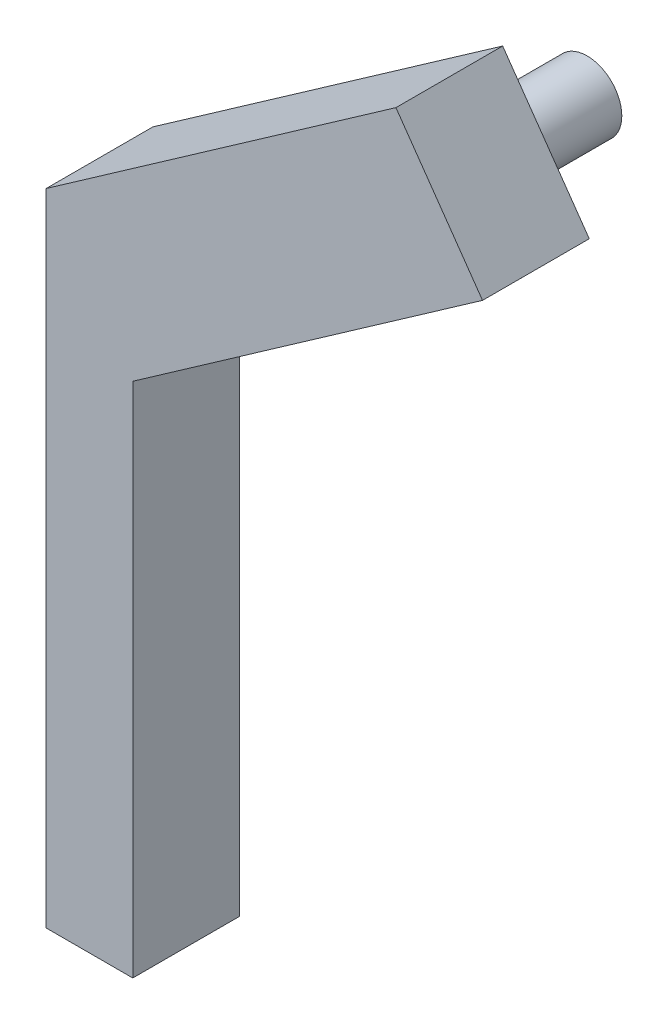
SolidWorks part; units mm, degrees
ref_plane "Front Plane" through (0, 0, 0) normal (0, 0, 1) x (1, 0, 0)
ref_plane "Top Plane" through (0, 0, 0) normal (0, 1, 0) x (1, 0, 0)
ref_plane "Right Plane" through (0, 0, 0) normal (1, 0, 0) x (0, 0, -1)
sketch "Sketch1" plane through (0, 0, 0) normal (0, 0, 1) x (1, 0, 0)
  line L0 (32.8506, -30.613) -> (65.6167, -7.67)
  line L1 (24.739, -19.0285) -> (32.8506, -19.0285)
  line L3 (24.739, -30.613) -> (32.8506, -30.613)
  line L4 (32.8506, -19.0285) -> (32.8506, -30.613)
  line L5 (65.6167, -7.67) -> (57.5051, 3.9146)
  line L6 (57.5051, 3.9146) -> (24.739, -19.0285)
  line L7 (24.739, -19.0285) -> (32.8506, -30.613)
  line L9 (24.739, -19.0285) -> (32.8506, -19.0285)
  line L10 (24.739, -19.0285) -> (24.739, -79.0285)
  line L11 (24.739, -79.0285) -> (32.8506, -79.0285)
  line L12 (32.8506, -19.0285) -> (32.8506, -79.0285)
  dimension "D1" = 125
  dimension "D4" = 40
  dimension "D5" = 60
extrude "Boss-Extrude1" add sketch "Sketch1" along normal blind 10
sketch "Sketch3" plane through (0, 0, 0) normal (0, 0, -1) x (-1, 0, 0)
  line L0 (-61.5609, -1.8777) -> (-28.7948, -24.8207) construction
  line L1 (-65.6167, -7.67) -> (-57.5051, 3.9146) construction
  line L3 (-32.8506, -30.613) -> (-24.739, -19.0285) construction
  circle A0 centre (-55.4173, -6.1795) radius 3.25
  circle A1 centre (-28.7948, -24.8207) radius 3.25
  point P6 (0, 0)
  point P9 (0, 0)
  point P11 (0, 0)
  point P12 (-28.7948, -24.8207)
  dimension "D3" = 6.5
  dimension "D1" = 7.5
extrude "Boss-Extrude3" add sketch "Sketch3" along normal blind 10
